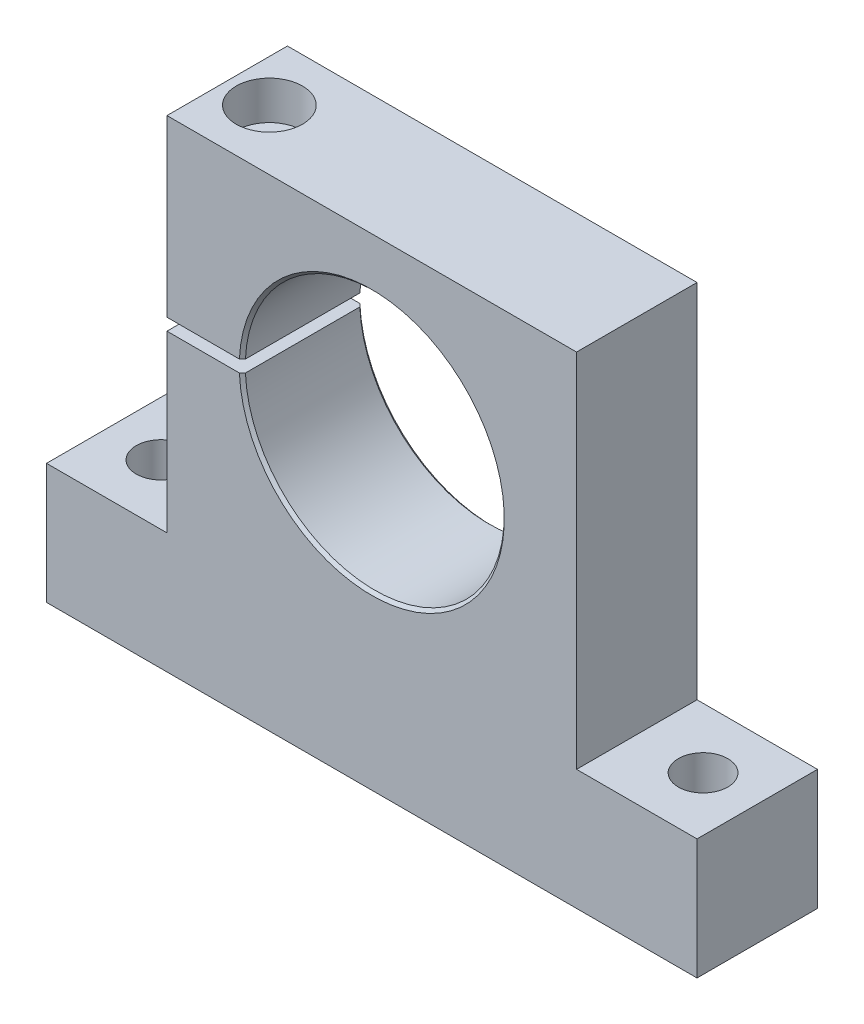
SolidWorks part; units mm, degrees
ref_plane "Piano frontale" through (0, 0, 0) normal (0, 0, 1) x (1, 0, 0)
ref_plane "Piano superiore" through (0, 0, 0) normal (0, 1, 0) x (1, 0, 0)
ref_plane "Piano destro" through (0, 0, 0) normal (1, 0, 0) x (0, 0, -1)
sketch "Schizzo1" plane through (0, 0, 0) normal (0, 0, 1) x (1, 0, 0)
  line L0 (0, 0) -> (108, 0)
  line L1 (0, 0) -> (0, 20)
  line L2 (0, 20) -> (20, 20)
  line L3 (20, 20) -> (20, 80)
  line L4 (20, 80) -> (88, 80)
  line L5 (54, 0) -> (54, 80) construction
  line L6 (108, 20) -> (88, 20)
  line L7 (108, 0) -> (108, 20)
  line L8 (88, 20) -> (88, 80)
  circle A0 centre (54, 50) radius 21.5
  dimension "D4" = 43
  dimension "D1" = 54
  dimension "D2" = 20
  dimension "D3" = 60
  dimension "D5" = 30
  dimension "D6" = 20
extrude "Estrusione-Estrusione1" add sketch "Schizzo1" along normal blind 20
sketch "Schizzo2" plane through (0, 20, 0) normal (0, 1, 0) x (1, 0, 0)
  line L0 (0, -10) -> (108, -10) construction
  line L1 (0, -20) -> (0, 0) construction
  line L2 (108, -20) -> (108, 0) construction
  line L6 (54, 0) -> (54, -20) construction
  line L7 (88, 0) -> (20, 0) construction
  line L8 (88, -20) -> (20, -20) construction
  point P12 (9, -10)
  point P19 (99, -10)
  dimension "D1" = 90
hole_wizard "Ø8.2 (8.2) Diameter Hole1" positions "Schizzo3D2" profile "Schizzo4" hole size "Ø8.2" standard "ISO" end condition through all
sketch3d "Schizzo3D2"
  point P0 (9, 20, 10)
  point P3 (99, 20, 10)
sketch "Schizzo4" plane through (9, 20, 10) normal (1, 0, 0) x (0, 0, 1)
  line L0 (0, 0) -> (0, 20)
  line L1 (0, 20) -> (4.1, 20)
  line L2 (4.1, 20) -> (4.1, 0)
  line L5 (4.1, 0) -> (0, 0)
  line L11 (0, -6.35) -> (0, 107.95) construction
  dimension "Thru Hole Dia." = 8.2
  dimension "Thru Hole Depth" = 20
sketch "Schizzo5" plane through (0, 80, 0) normal (0, 1, 0) x (1, 0, 0)
  line L0 (20, -10) -> (80.6806, -10) construction
  line L1 (20, -20) -> (20, 0) construction
  line L2 (0, -10) -> (108, -10) construction
  line L3 (20, -20) -> (20, 0) construction
  point P6 (27, -10)
  dimension "D1" = 7
hole_wizard "CBORE for M6 Hex Socket Head Cap Screw1" positions "Schizzo3D3" profile "Schizzo6" counterbore size "M6" standard "ISO"
sketch3d "Schizzo3D3"
  point P0 (27, 80, 10)
sketch "Schizzo6" plane through (27, 80, 10) normal (1, 0, 0) x (0, 0, 1)
  line L0 (0, 0) -> (0, 51.9828)
  line L1 (0, 51.9828) -> (3.3, 50)
  line L2 (3.3, 50) -> (3.3, 6.4)
  line L3 (3.3, 6.4) -> (5.5, 6.4)
  line L4 (5.5, 6.4) -> (5.5, 0)
  line L5 (5.5, 0) -> (0, 0)
  line L10 (0, 51.9828) -> (-3.3, 50) construction
  line L11 (0, -6.35) -> (0, 107.95) construction
  dimension "Hole Dia." = 6.6
  dimension "Hole Depth" = 50
  dimension "C'Bore Dia." = 11
  dimension "C'Bore Depth" = 6.4
  dimension "Drill Angle" = 118
sketch "Schizzo7" plane through (0, 0, 0) normal (0, 0, -1) x (-1, 0, 0)
  line L0 (-54, 50) -> (-5.4537, 50) construction
  line L2 (-19.9047, 49) -> (-35.4261, 49)
  line L3 (-19.9047, 49) -> (-19.9047, 51)
  line L4 (-19.9047, 51) -> (-35.4261, 51)
  line L5 (-35.4261, 49) -> (-35.4261, 51)
  line L6 (-19.9047, 49) -> (-35.4261, 51) construction
  line L7 (-19.9047, 51) -> (-35.4261, 49) construction
  point P3 (-27.6654, 50)
  dimension "D1" = 2
extrude "Taglio-Estrusione1" cut sketch "Schizzo7" against normal through all
chamfer "Chamfer1" distance 0.5 angle 45 1 edges at (75.5, 50, 0)
chamfer "Chamfer2" distance 0.5 angle 45 1 edges at (75.5, 50, 20)
